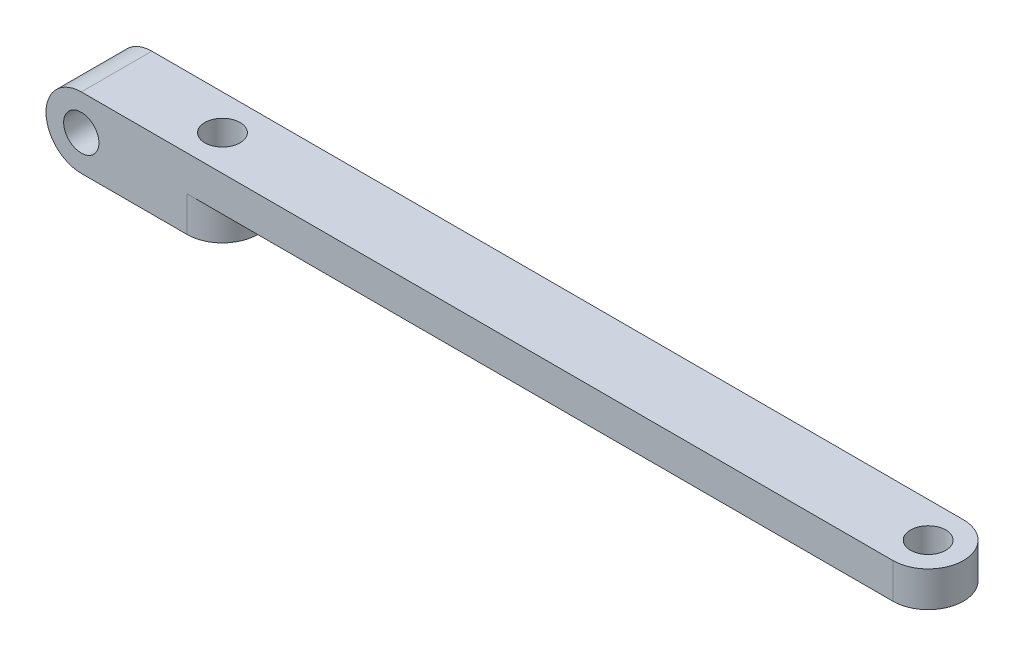
SolidWorks part; units mm, degrees
ref_plane "Front Plane" through (0, 0, 0) normal (0, 0, 1) x (1, 0, 0)
ref_plane "Top Plane" through (0, 0, 0) normal (0, 1, 0) x (1, 0, 0)
ref_plane "Right Plane" through (0, 0, 0) normal (1, 0, 0) x (0, 0, -1)
sketch "Sketch1" plane through (0, 0, 0) normal (0, 0, 1) x (1, 0, 0)
  circle A0 centre (0, 0) radius 2
extrude "Boss-Extrude1" add sketch "Sketch1" along normal blind 4
sketch "Sketch2" plane through (0, 0, 4) normal (0, 0, 1) x (1, 0, 0)
  line L0 (0, 2) -> (3, 2)
  line L1 (3, 2) -> (3, -2)
  line L2 (3, -2) -> (0, -2)
  circle A0 centre (0, 0) radius 2
  arc A1 (0, 2) -> (0, -2) centre (0, 0) cw
  circle M3 centre (0, 0) radius 2
  dimension "D1" = 4
  dimension "D2" = 3
extrude "Boss-Extrude2" add sketch "Sketch2" against normal blind 4 contours L2 L1 L0 M3
sketch "Sketch3" plane through (0, 0, 4) normal (0, 0, 1) x (1, 0, 0)
  circle A0 centre (0, 0) radius 1
extrude "Cut-Extrude1" cut sketch "Sketch3" against normal through all
ref_plane "Plane1" through (0, 0, 0) normal (0, 1, 0) x (1, 0, 0)
sketch "Sketch7" plane through (0, 0, 0) normal (0, 1, 0) x (1, 0, 0)
  line L4 (3, 0) -> (3, -4)
  line L5 (3, -4) -> (6, -4)
  line L7 (6, 0) -> (3, 0)
  arc A0 (6, 0) -> (6, -4) centre (6, -2) cw
  circle A1 centre (6, -2) radius 1
  dimension "D3" = 2
  dimension "D4" = 2
  dimension "D5" = 2
  dimension "D6" = 2
  dimension "D1" = 3
  dimension "D2" = 3
  dimension "D7" = 3
extrude "Boss-Extrude4" add sketch "Sketch7" along normal mid plane 4
sketch "Sketch8" plane through (0, 0, 0) normal (0, 1, 0) x (1, 0, 0)
  line L0 (46, -2) -> (6, -2) construction
  line L1 (46, -4) -> (6, -4)
  line L2 (46, 0) -> (6, 0)
  arc A0 (46, -4) -> (46, 0) centre (46, -2) ccw
  arc A1 (6, 0) -> (6, -4) centre (6, -2) ccw
  circle A2 centre (46, -2) radius 1
  circle A3 centre (6, -2) radius 1
  point P3 (26, -2)
  dimension "D1" = 2
  dimension "D3" = 2
  dimension "D4" = 2
  dimension "D2" = 40
extrude "Boss-Extrude5" add sketch "Sketch8" along normal blind 2
